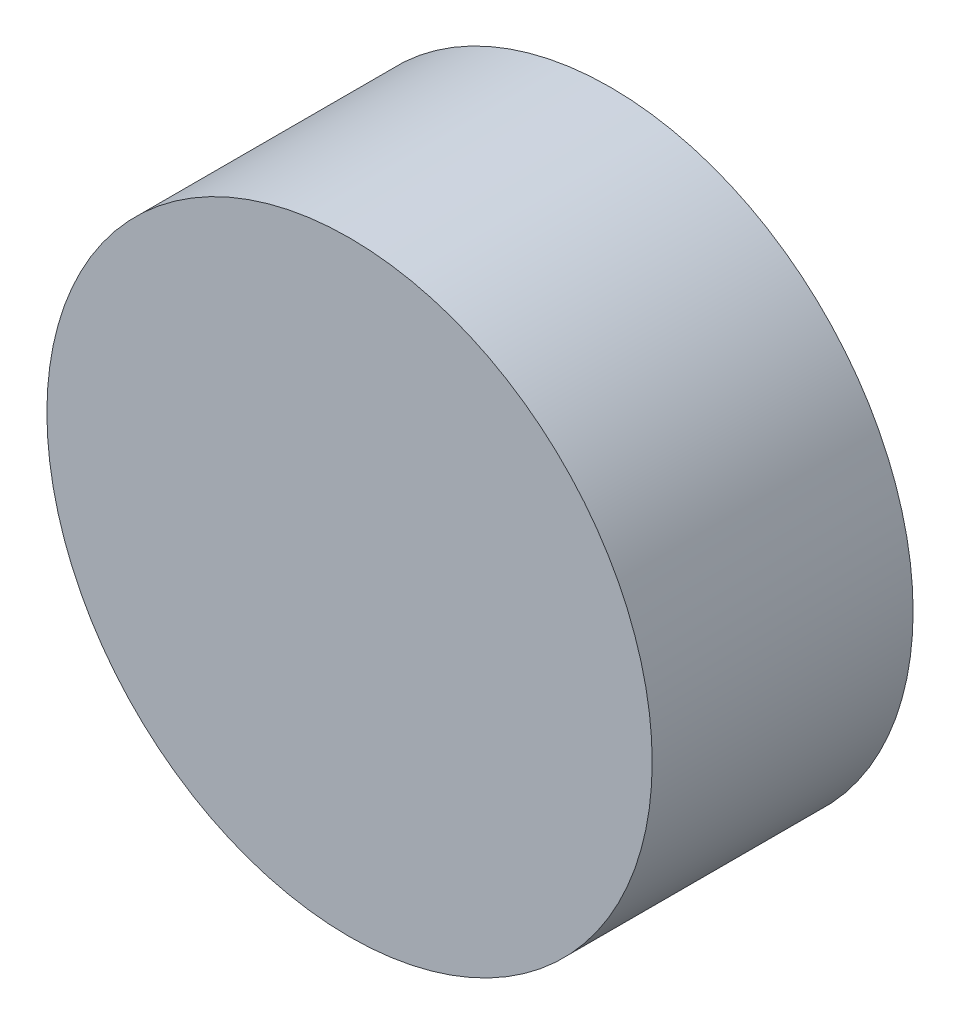
SolidWorks part; units mm, degrees
ref_plane "Front Plane" through (0, 0, 0) normal (0, 0, 1) x (1, 0, 0)
ref_plane "Top Plane" through (0, 0, 0) normal (0, 1, 0) x (1, 0, 0)
ref_plane "Right Plane" through (0, 0, 0) normal (1, 0, 0) x (0, 0, -1)
sketch "Sketch1" plane through (0, 0, 0) normal (0, 0, 1) x (1, 0, 0)
  circle A0 centre (0, 0) radius 29
  dimension "D1" = 58
extrude "Boss-Extrude2" add sketch "Sketch1" along normal blind 25
